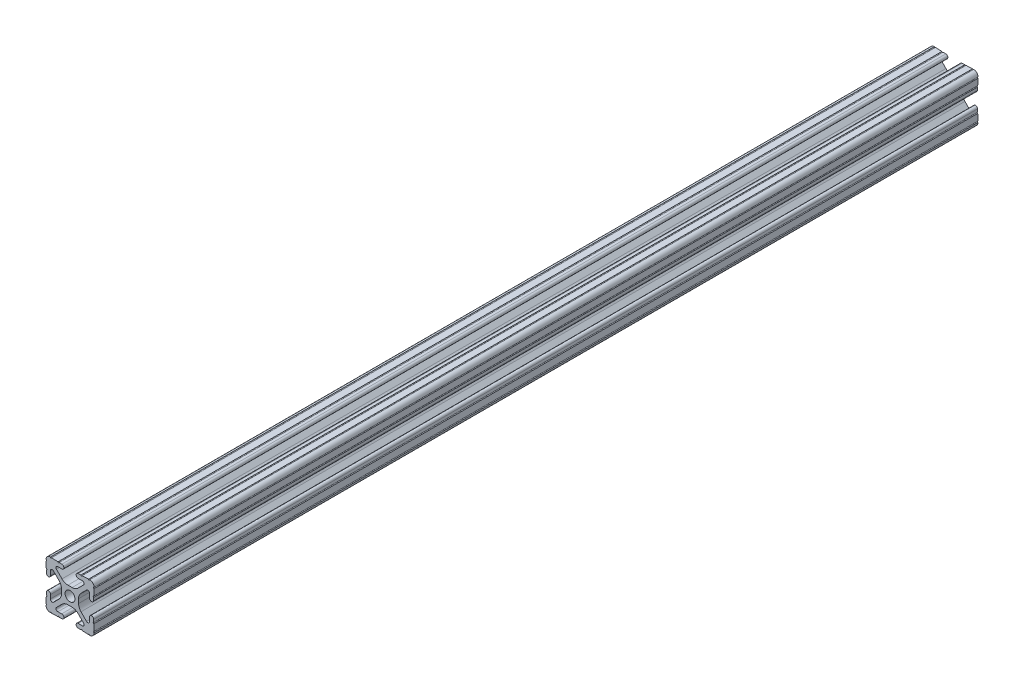
SolidWorks part; units mm, degrees
ref_plane "Front Plane" through (0, 0, 0) normal (0, 0, 1) x (1, 0, 0)
ref_plane "Top Plane" through (0, 0, 0) normal (0, 1, 0) x (1, 0, 0)
ref_plane "Right Plane" through (0, 0, 0) normal (1, 0, 0) x (0, 0, -1)
sketch "Sketch1" plane through (0, 0, 0) normal (0, 0, 1) x (1, 0, 0)
  line L0 (0, 12.7) -> (-12.7814, 12.7) construction
  line L1 (-4.5085, 0) -> (-4.5085, 2.9459)
  line L2 (-6.0437, 12.5461) -> (-10.0976, 12.6876) construction
  line L3 (-11.5616, 12.4229) -> (-4.3159, 12.1699) construction
  line L4 (-6.4364, 10.3486) -> (-6.3592, 12.5571) construction
  line L6 (-2.9459, 4.5085) -> (0, 4.5085)
  line L7 (0, 0) -> (0, 12.7) construction
  line L8 (0, 0) -> (-12.7814, 0) construction
  line L9 (0.7813, 0.7813) -> (-0.7813, -0.7813) construction
  line L10 (-2.9459, 4.5085) -> (-7.1484, 8.711)
  line L11 (-4.5085, 2.9459) -> (-8.711, 7.1484)
  line L13 (0, 0) -> (-12.7814, 12.7814) construction
  line L14 (-10.4131, 12.6987) -> (-4.3048, 12.4853)
  line L15 (-4.3048, 12.4853) -> (-4.382, 10.2769) construction
  line L16 (-4.382, 10.2769) -> (-6.4364, 10.3486)
  line L17 (-12.6987, 10.4131) -> (-12.4853, 4.3048)
  line L18 (-10.2769, 4.382) -> (-10.3486, 6.4364)
  circle A0 centre (0, 0) radius 2.6035
  arc A1 (-4.382, 10.2769) -> (-4.3048, 12.4853) centre (-4.3434, 11.3811) ccw
  arc A2 (-7.1484, 8.711) -> (-6.4364, 10.3486) centre (-6.4698, 9.3896) cw
  arc A3 (-8.711, 7.1484) -> (-10.3486, 6.4364) centre (-9.3896, 6.4698) ccw
  arc A4 (-10.2769, 4.382) -> (-12.4853, 4.3048) centre (-11.3811, 4.3434) cw
  arc A5 (-10.4131, 12.6987) -> (-12.6987, 10.4131) centre (-10.4902, 10.4902) ccw
  arc A6 (-10.4131, 12.6987) -> (-9.7821, 12.6766) centre (-10.0976, 12.6876) ccw
  arc A7 (-6.3592, 12.5571) -> (-5.7282, 12.5351) centre (-6.0437, 12.5461) ccw
  arc A8 (-12.5571, 6.3592) -> (-12.5351, 5.7282) centre (-12.5461, 6.0437) cw
  arc A9 (-12.6987, 10.4131) -> (-12.6766, 9.7821) centre (-12.6876, 10.0976) cw
  dimension "D1" = 5.207
  dimension "D5" = 14.859
  dimension "D9" = 2
  dimension "D2" = 25.4
  dimension "D12" = 0.6314
  dimension "D10" = 2.2098
  dimension "D3" = 9.017
  dimension "D4" = 9.017
  dimension "D6" = 25.4
  dimension "D7" = 6.477
  dimension "D8" = 2.2098
  dimension "D11" = 12.7
sketch "Sketch3" plane through (0, 0, 0) normal (0, 0, 1) x (1, 0, 0)
  line L0 (-2.9459, 4.5085) -> (0, 4.5085) construction
  line L1 (-2.9459, 4.5085) -> (-7.1484, 8.711) construction
  line L2 (-4.382, 10.2769) -> (-6.4364, 10.3486) construction
  line L3 (-10.4131, 12.6987) -> (-4.3048, 12.4853) construction
  line L4 (-4.5085, 0) -> (-4.5085, 2.9459) construction
  line L5 (-4.5085, 2.9459) -> (-8.711, 7.1484) construction
  line L6 (-10.2769, 4.382) -> (-10.3486, 6.4364) construction
  line L7 (-12.6987, 10.4131) -> (-12.4853, 4.3048) construction
  line L8 (-1.1153, 4.5085) -> (1.1153, 4.5085)
  line L9 (-4.2404, 5.803) -> (-7.1484, 8.711)
  line L10 (-4.382, 10.2769) -> (-6.4364, 10.3486)
  line L11 (-9.7821, 12.6766) -> (-6.3592, 12.5571)
  line L12 (-4.5085, -1.1153) -> (-4.5085, 1.1153)
  line L13 (-5.803, 4.2404) -> (-8.711, 7.1484)
  line L14 (-10.2769, 4.382) -> (-10.3486, 6.4364)
  line L15 (-12.6766, 9.7821) -> (-12.5571, 6.3592)
  line L16 (-5.7282, 12.5351) -> (-4.3048, 12.4853)
  line L17 (-12.5351, 5.7282) -> (-12.4853, 4.3048)
  line L18 (0, 0) -> (0, 12.7) construction
  line L19 (0, 0) -> (-12.7814, 0) construction
  line L20 (12.5351, 5.7282) -> (12.4853, 4.3048)
  line L21 (5.7282, 12.5351) -> (4.3048, 12.4853)
  line L22 (12.6766, 9.7821) -> (12.5571, 6.3592)
  line L23 (10.2769, 4.382) -> (10.3486, 6.4364)
  line L24 (5.803, 4.2404) -> (8.711, 7.1484)
  line L25 (4.5085, -1.1153) -> (4.5085, 1.1153)
  line L26 (9.7821, 12.6766) -> (6.3592, 12.5571)
  line L27 (4.382, 10.2769) -> (6.4364, 10.3486)
  line L28 (4.2404, 5.803) -> (7.1484, 8.711)
  line L29 (4.2404, -5.803) -> (7.1484, -8.711)
  line L30 (4.382, -10.2769) -> (6.4364, -10.3486)
  line L31 (9.7821, -12.6766) -> (6.3592, -12.5571)
  line L32 (5.803, -4.2404) -> (8.711, -7.1484)
  line L33 (10.2769, -4.382) -> (10.3486, -6.4364)
  line L34 (12.6766, -9.7821) -> (12.5571, -6.3592)
  line L35 (5.7282, -12.5351) -> (4.3048, -12.4853)
  line L36 (12.5351, -5.7282) -> (12.4853, -4.3048)
  line L37 (-12.5351, -5.7282) -> (-12.4853, -4.3048)
  line L38 (-5.7282, -12.5351) -> (-4.3048, -12.4853)
  line L39 (-12.6766, -9.7821) -> (-12.5571, -6.3592)
  line L40 (-10.2769, -4.382) -> (-10.3486, -6.4364)
  line L41 (-5.803, -4.2404) -> (-8.711, -7.1484)
  line L42 (-9.7821, -12.6766) -> (-6.3592, -12.5571)
  line L43 (-4.382, -10.2769) -> (-6.4364, -10.3486)
  line L44 (-4.2404, -5.803) -> (-7.1484, -8.711)
  line L45 (-1.1153, -4.5085) -> (1.1153, -4.5085)
  arc A0 (-10.4131, 12.6987) -> (-9.7821, 12.6766) centre (-10.0976, 12.6876) ccw construction
  arc A1 (-6.4364, 10.3486) -> (-7.1484, 8.711) centre (-6.4698, 9.3896) ccw construction
  arc A2 (-4.382, 10.2769) -> (-4.3048, 12.4853) centre (-4.3434, 11.3811) ccw construction
  arc A3 (-8.711, 7.1484) -> (-10.3486, 6.4364) centre (-9.3896, 6.4698) ccw construction
  arc A4 (-12.4853, 4.3048) -> (-10.2769, 4.382) centre (-11.3811, 4.3434) ccw construction
  arc A5 (-6.3592, 12.5571) -> (-5.7282, 12.5351) centre (-6.0437, 12.5461) ccw construction
  arc A6 (-10.4131, 12.6987) -> (-12.6987, 10.4131) centre (-10.4902, 10.4902) ccw construction
  arc A7 (-12.6766, 9.7821) -> (-12.6987, 10.4131) centre (-12.6876, 10.0976) ccw construction
  arc A8 (-12.5351, 5.7282) -> (-12.5571, 6.3592) centre (-12.5461, 6.0437) ccw construction
  arc A9 (-10.4131, 12.6987) -> (-9.7821, 12.6766) centre (-10.0976, 12.6876) ccw
  arc A10 (-6.4364, 10.3486) -> (-7.1484, 8.711) centre (-6.4698, 9.3896) ccw
  arc A11 (-4.382, 10.2769) -> (-4.3048, 12.4853) centre (-4.3434, 11.3811) ccw
  arc A12 (-8.711, 7.1484) -> (-10.3486, 6.4364) centre (-9.3896, 6.4698) ccw
  arc A13 (-12.4853, 4.3048) -> (-10.2769, 4.382) centre (-11.3811, 4.3434) ccw
  arc A14 (-6.3592, 12.5571) -> (-5.7282, 12.5351) centre (-6.0437, 12.5461) ccw
  arc A15 (-10.4131, 12.6987) -> (-12.6987, 10.4131) centre (-10.4902, 10.4902) ccw
  arc A16 (-12.6766, 9.7821) -> (-12.6987, 10.4131) centre (-12.6876, 10.0976) ccw
  arc A17 (-12.5351, 5.7282) -> (-12.5571, 6.3592) centre (-12.5461, 6.0437) ccw
  arc A18 (-1.1153, 4.5085) -> (-4.2404, 5.803) centre (-1.1153, 8.9281) cw
  arc A19 (4.5085, 1.1153) -> (5.803, 4.2404) centre (8.9281, 1.1153) cw
  arc A20 (1.1153, 4.5085) -> (4.2404, 5.803) centre (1.1153, 8.9281) ccw
  arc A21 (-4.5085, 1.1153) -> (-5.803, 4.2404) centre (-8.9281, 1.1153) ccw
  arc A22 (12.5351, 5.7282) -> (12.5571, 6.3592) centre (12.5461, 6.0437) cw
  arc A23 (12.6766, 9.7821) -> (12.6987, 10.4131) centre (12.6876, 10.0976) cw
  arc A24 (10.4131, 12.6987) -> (12.6987, 10.4131) centre (10.4902, 10.4902) cw
  arc A25 (6.3592, 12.5571) -> (5.7282, 12.5351) centre (6.0437, 12.5461) cw
  arc A26 (12.4853, 4.3048) -> (10.2769, 4.382) centre (11.3811, 4.3434) cw
  arc A27 (8.711, 7.1484) -> (10.3486, 6.4364) centre (9.3896, 6.4698) cw
  arc A28 (4.382, 10.2769) -> (4.3048, 12.4853) centre (4.3434, 11.3811) cw
  arc A29 (6.4364, 10.3486) -> (7.1484, 8.711) centre (6.4698, 9.3896) cw
  arc A30 (10.4131, 12.6987) -> (9.7821, 12.6766) centre (10.0976, 12.6876) cw
  arc A31 (10.4131, -12.6987) -> (9.7821, -12.6766) centre (10.0976, -12.6876) ccw
  arc A32 (6.4364, -10.3486) -> (7.1484, -8.711) centre (6.4698, -9.3896) ccw
  arc A33 (4.382, -10.2769) -> (4.3048, -12.4853) centre (4.3434, -11.3811) ccw
  arc A34 (8.711, -7.1484) -> (10.3486, -6.4364) centre (9.3896, -6.4698) ccw
  arc A35 (12.4853, -4.3048) -> (10.2769, -4.382) centre (11.3811, -4.3434) ccw
  arc A36 (6.3592, -12.5571) -> (5.7282, -12.5351) centre (6.0437, -12.5461) ccw
  arc A37 (10.4131, -12.6987) -> (12.6987, -10.4131) centre (10.4902, -10.4902) ccw
  arc A38 (12.6766, -9.7821) -> (12.6987, -10.4131) centre (12.6876, -10.0976) ccw
  arc A39 (12.5351, -5.7282) -> (12.5571, -6.3592) centre (12.5461, -6.0437) ccw
  arc A40 (-4.5085, -1.1153) -> (-5.803, -4.2404) centre (-8.9281, -1.1153) cw
  arc A41 (1.1153, -4.5085) -> (4.2404, -5.803) centre (1.1153, -8.9281) cw
  arc A42 (4.5085, -1.1153) -> (5.803, -4.2404) centre (8.9281, -1.1153) ccw
  arc A43 (-1.1153, -4.5085) -> (-4.2404, -5.803) centre (-1.1153, -8.9281) ccw
  arc A44 (-12.5351, -5.7282) -> (-12.5571, -6.3592) centre (-12.5461, -6.0437) cw
  arc A45 (-12.6766, -9.7821) -> (-12.6987, -10.4131) centre (-12.6876, -10.0976) cw
  arc A46 (-10.4131, -12.6987) -> (-12.6987, -10.4131) centre (-10.4902, -10.4902) cw
  arc A47 (-6.3592, -12.5571) -> (-5.7282, -12.5351) centre (-6.0437, -12.5461) cw
  arc A48 (-12.4853, -4.3048) -> (-10.2769, -4.382) centre (-11.3811, -4.3434) cw
  arc A49 (-8.711, -7.1484) -> (-10.3486, -6.4364) centre (-9.3896, -6.4698) cw
  arc A50 (-4.382, -10.2769) -> (-4.3048, -12.4853) centre (-4.3434, -11.3811) cw
  arc A51 (-6.4364, -10.3486) -> (-7.1484, -8.711) centre (-6.4698, -9.3896) cw
  arc A52 (-10.4131, -12.6987) -> (-9.7821, -12.6766) centre (-10.0976, -12.6876) cw
  circle A53 centre (0, 0) radius 2.6035 construction
  circle A54 centre (0, 0) radius 2.6035
  point P135 (4.5085, 0)
  dimension "D2" = 4.4196
extrude "Extrude1" add sketch "Sketch3" along normal mid plane 467.175
equation "\"D10@Sketch1\" = \"D8@Sketch1\""
equation "\"D11@Sketch1\" = \"D6@Sketch1\"/2"
equation "\"D12@Sketch1\" = \"D8@Sketch1\"/3.5"
equation "\"D2@Sketch3\" = \"D8@Sketch1\"*2"
